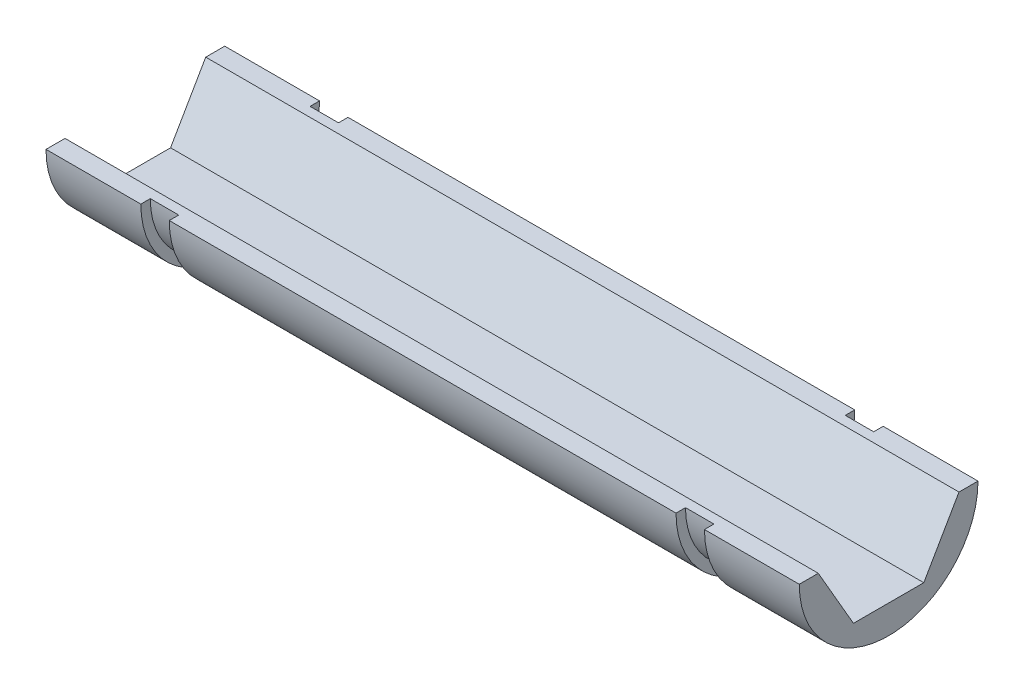
SolidWorks part; units mm, degrees
ref_plane "Front Plane" through (0, 0, 0) normal (0, 0, 1) x (1, 0, 0)
ref_plane "Top Plane" through (0, 0, 0) normal (0, 1, 0) x (1, 0, 0)
ref_plane "Right Plane" through (0, 0, 0) normal (1, 0, 0) x (0, 0, -1)
sketch "Sketch1" plane through (0, 0, 0) normal (1, 0, 0) x (0, 0, -1)
  line L1 (7.4203, 0) -> (3.7102, 6.4262)
  line L2 (3.7102, 6.4262) -> (-3.7102, 6.4262)
  line L3 (-3.7102, 6.4262) -> (-7.4203, 0)
  line L4 (-7.4203, 0) -> (-3.7102, -6.4262)
  line L5 (-3.7102, -6.4262) -> (3.7102, -6.4262)
  line L6 (3.7102, -6.4262) -> (7.4203, 0)
  circle A0 centre (0, 0) radius 6.4262 construction
  circle A1 centre (0, 0) radius 9.4262
  point P11 (7.1689, -1.9152)
  dimension "D1" = 12.8524
  dimension "D2" = 3
extrude "Boss-Extrude1" add sketch "Sketch1" along normal blind 79.4512 contours L5 L6 L1 L2 L3 L4 | A1
ref_plane "Plane1" through (39.7256, 0, 0) normal (-1, 0, 0) x (0, 0, 1)
sketch "Sketch2" plane through (0, 0, 0) normal (0, 0, 1) x (1, 0, 0)
  line L0 (79.4512, 9.4262) -> (0, 9.4262) construction
  line L1 (10, 9.4262) -> (13, 9.4262)
  line L2 (10, 9.4262) -> (10, 8.4262)
  line L3 (10, 8.4262) -> (13, 8.4262)
  line L4 (13, 9.4262) -> (13, 8.4262)
  line L5 (0, 9.4262) -> (0, -9.4262) construction
  point P6 (8.3409, 8.4262)
  dimension "D1" = 1
  dimension "D2" = 3
  dimension "D3" = 10
ref_axis "Axis1" through (-1.5494, 0, 0) along (1, 0, 0)
revolve "Cut-Revolve1" cut sketch "Sketch2" angle 360 about axis through (-1.5494, 0, 0) along (1, 0, 0)
mirror "Mirror1" about plane through (39.7256, 0, 0) normal (-1, 0, 0) of "Cut-Revolve1"
split "Split1" trim tools "Top Plane" bodies to split 103 resulting bodies 104
